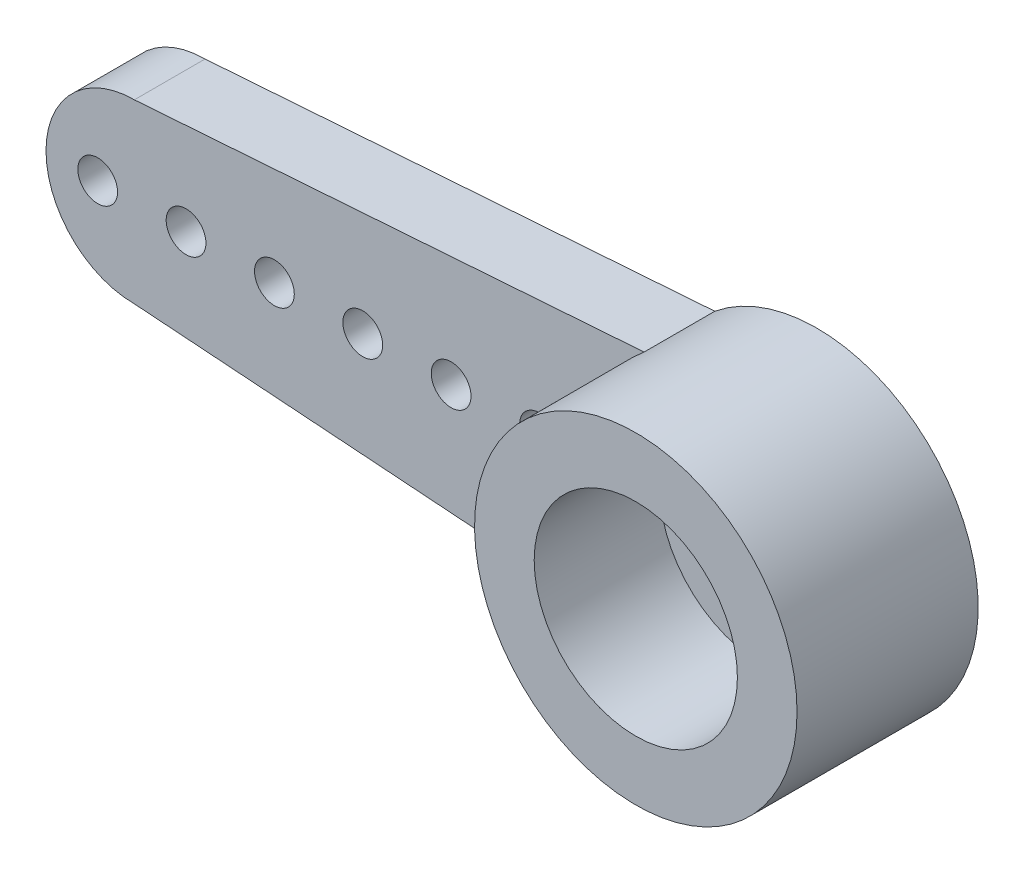
SolidWorks part; units mm, degrees
material "Polietileno reticulado"
ref_plane "Plano frontal" through (0, 0, 0) normal (0, 0, 1) x (1, 0, 0)
ref_plane "Plano superior" through (0, 0, 0) normal (0, 1, 0) x (1, 0, 0)
ref_plane "Plano direito" through (0, 0, 0) normal (1, 0, 0) x (0, 0, -1)
sketch "Esboço1" plane through (0, 0, 0) normal (0, 0, 1) x (1, 0, 0)
  line L0 (-13.85, 2) -> (-2.3112, 2.825)
  line L1 (0, 0) -> (-13.85, 0) construction
  line L2 (-13.85, -2) -> (-2.3112, -2.825)
  line L3 (-2.3112, 2.825) -> (-2.3112, -2.825) construction
  arc A0 (-2.3112, -2.825) -> (-2.3112, 2.825) centre (0, 0) ccw
  arc A1 (-13.85, 2) -> (-13.85, -2) centre (-13.85, 0) ccw
  point P8 (-3.65, 0)
  dimension "D1" = 7.3
  dimension "D3" = 4
  dimension "D2" = 13.85
  dimension "D4" = 5.65
extrude "Ressalto-extrusão1" add sketch "Esboço1" along normal blind 1.6
sketch "Esboço2" plane through (0, 0, 1.6) normal (0, 0, 1) x (1, 0, 0)
  circle A0 centre (0, 0) radius 3.65
extrude "Ressalto-extrusão2" add sketch "Esboço2" along normal blind 2.5
sketch "Esboço3" plane through (0, 0, 4.1) normal (0, 0, 1) x (1, 0, 0)
  circle A0 centre (0, 0) radius 2.3
  dimension "D1" = 4.6
extrude "Corte-extrusão1" cut sketch "Esboço3" against normal blind 2.84
sketch "Esboço4" plane through (0, 0, 1.6) normal (0, 0, 1) x (1, 0, 0)
  line L0 (-3.65, 0) -> (-4.68, 0) construction
  arc A0 (-2.3112, 2.825) -> (-2.3112, -2.825) centre (0, 0) ccw construction
  circle A1 centre (-4.68, 0) radius 0.45
  circle A2 centre (-6.68, 0) radius 0.45
  circle A3 centre (-8.68, 0) radius 0.45
  circle A4 centre (-10.68, 0) radius 0.45
  circle A5 centre (-12.68, 0) radius 0.45
  circle A6 centre (-14.68, 0) radius 0.45
  dimension "D1" = 6
  dimension "D2" = 0.9
extrude "Corte-extrusão2" cut sketch "Esboço4" against normal up to next
sketch "Esboço5" plane through (0, 0, 0) normal (0, 0, -1) x (-1, 0, 0)
  circle A0 centre (0, 0) radius 1.3
  dimension "D1" = 2.6
extrude "Corte-extrusão3" cut sketch "Esboço5" against normal blind 2.84
sketch "Esboço6" plane through (0, 0, 0) normal (0, 0, -1) x (-1, 0, 0)
  circle A0 centre (0, 0) radius 2.45
extrude "Corte-extrusão4" cut sketch "Esboço6" against normal blind 0.78
